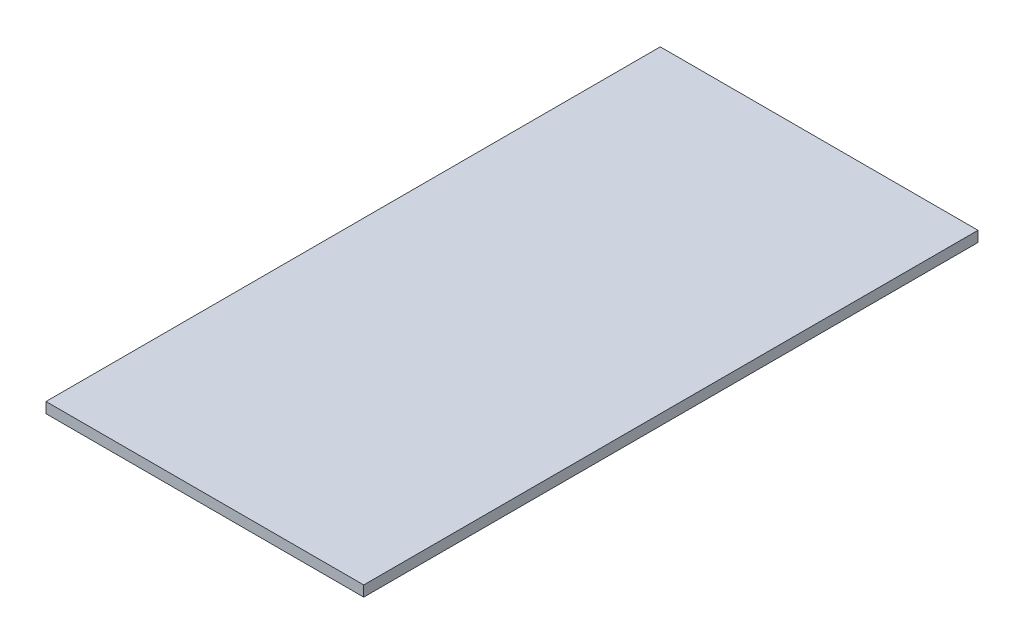
SolidWorks part; units mm, degrees
ref_plane "Front Plane" through (0, 0, 0) normal (0, 0, 1) x (1, 0, 0)
ref_plane "Top Plane" through (0, 0, 0) normal (0, 1, 0) x (1, 0, 0)
ref_plane "Right Plane" through (0, 0, 0) normal (1, 0, 0) x (0, 0, -1)
sketch "Sketch1" plane through (0, 0, 0) normal (0, 1, 0) x (1, 0, 0)
  line L1 (0, 0) -> (30, 0)
  line L2 (0, 0) -> (0, 58)
  line L3 (0, 58) -> (30, 58)
  line L4 (30, 0) -> (30, 58)
  dimension "D1" = 30
  dimension "D2" = 58
extrude "Boss-Extrude1" add sketch "Sketch1" along normal blind 1
